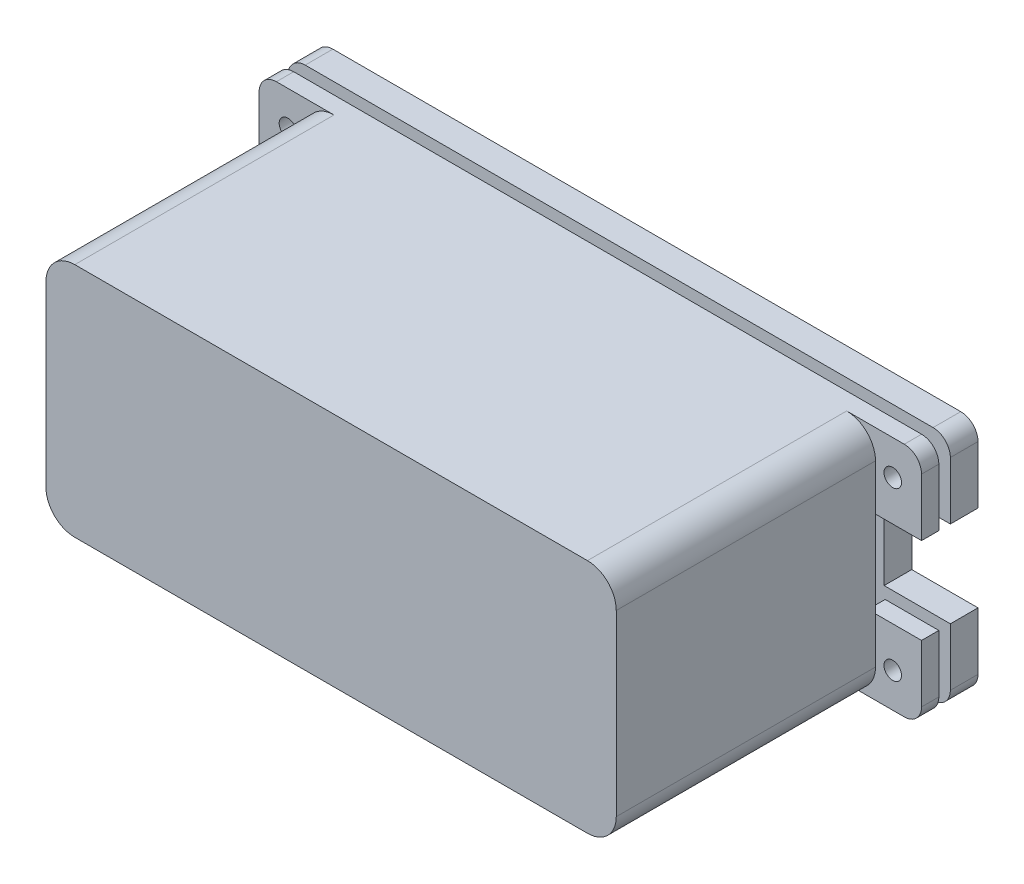
SolidWorks part; units mm, degrees
material "ABS"
ref_plane "前视基准面" through (0, 0, 0) normal (0, 0, 1) x (1, 0, 0)
ref_plane "上视基准面" through (0, 0, 0) normal (0, 1, 0) x (1, 0, 0)
ref_plane "右视基准面" through (0, 0, 0) normal (1, 0, 0) x (0, 0, -1)
other "Configuration Table"
sketch "草图1" plane through (0, 0, 0) normal (0, 0, 1) x (1, 0, 0)
  line L1 (-57.5, -20.5) -> (57.5, -20.5)
  line L2 (-57.5, -20.5) -> (-57.5, 20.5)
  line L3 (-57.5, 20.5) -> (57.5, 20.5)
  line L4 (57.5, -20.5) -> (57.5, 20.5)
  line L5 (-57.5, -20.5) -> (57.5, 20.5) construction
  line L6 (-57.5, 20.5) -> (57.5, -20.5) construction
  point P0 (0, 0)
  dimension "D1" = 115
  dimension "D2" = 41
extrude "凸台-拉伸1" add sketch "草图1" along normal blind 4.8
fillet "圆角1" radius 3 4 edges at (-57.5, -20.5, 2.4) (-57.5, 20.5, 2.4) (57.5, -20.5, 2.4) (57.5, 20.5, 2.4)
sketch "草图2" plane through (0, 0, 4.8) normal (0, 0, 1) x (1, 0, 0)
  line L0 (57.5, -17.5) -> (57.5, 17.5) construction
  line L1 (51, -7.5) -> (64, -7.5)
  line L2 (51, -7.5) -> (51, 7.5)
  line L3 (51, 7.5) -> (64, 7.5)
  line L4 (64, -7.5) -> (64, 7.5)
  line L5 (51, -7.5) -> (64, 7.5) construction
  line L6 (51, 7.5) -> (64, -7.5) construction
  line L8 (-52.5, -14.5) -> (52.5, -14.5) construction
  line L9 (-52.5, -14.5) -> (-52.5, 14.5) construction
  line L10 (-52.5, 14.5) -> (52.5, 14.5) construction
  line L11 (52.5, -14.5) -> (52.5, 14.5) construction
  line L12 (-52.5, -14.5) -> (52.5, 14.5) construction
  line L13 (-52.5, 14.5) -> (52.5, -14.5) construction
  circle A0 centre (52.5, 14.5) radius 1.52
  circle A1 centre (-52.5, 14.5) radius 1.52
  circle A2 centre (-52.5, -14.5) radius 1.52
  circle A3 centre (52.5, -14.5) radius 1.52
  point P0 (57.5, 0)
  point P7 (0, 0)
  dimension "D5" = 3.04
  dimension "D1" = 105
  dimension "D2" = 29
  dimension "D3" = 13
  dimension "D4" = 15
extrude "切除-拉伸1" cut sketch "草图2" against normal blind 55
ref_plane "基准面1" through (0, 0, 6.8) normal (0, 0, 1) x (1, 0, 0)
sketch "草图4" plane through (0, 0, 6.8) normal (0, 0, 1) x (1, 0, 0)
  line L8 (57.5, -17.5) -> (57.5, -7.5)
  line L9 (57.5, -7.5) -> (51, -7.5)
  line L10 (51, -7.5) -> (51, 7.5)
  line L11 (51, 7.5) -> (57.5, 7.5)
  line L12 (57.5, 7.5) -> (57.5, 17.5)
  line L13 (54.5, 20.5) -> (-54.5, 20.5)
  line L14 (-57.5, 17.5) -> (-57.5, -17.5)
  line L15 (-54.5, -20.5) -> (54.5, -20.5)
  line L16 (57.5, -17.5) -> (57.5, -7.5)
  line L17 (57.5, -7.5) -> (51, -7.5)
  line L18 (51, -7.5) -> (51, 7.5)
  line L19 (51, 7.5) -> (57.5, 7.5)
  line L20 (57.5, 7.5) -> (57.5, 17.5)
  line L21 (54.5, 20.5) -> (-54.5, 20.5)
  line L22 (-57.5, 17.5) -> (-57.5, -17.5)
  line L23 (-54.5, -20.5) -> (54.5, -20.5)
  arc A4 (57.5, 17.5) -> (54.5, 20.5) centre (54.5, 17.5) ccw
  arc A5 (-54.5, 20.5) -> (-57.5, 17.5) centre (-54.5, 17.5) ccw
  arc A6 (-57.5, -17.5) -> (-54.5, -20.5) centre (-54.5, -17.5) ccw
  arc A7 (54.5, -20.5) -> (57.5, -17.5) centre (54.5, -17.5) ccw
  arc A8 (57.5, 17.5) -> (54.5, 20.5) centre (54.5, 17.5) ccw
  arc A9 (-54.5, 20.5) -> (-57.5, 17.5) centre (-54.5, 17.5) ccw
  arc A10 (-57.5, -17.5) -> (-54.5, -20.5) centre (-54.5, -17.5) ccw
  arc A11 (54.5, -20.5) -> (57.5, -17.5) centre (54.5, -17.5) ccw
  dimension "D1" = 0
extrude "凸台-拉伸2" add sketch "草图4" along normal blind 3 separate body
sketch "草图5" plane through (0, 0, 9.8) normal (0, 0, 1) x (1, 0, 0)
  line L0 (54.5, 20.5) -> (-54.5, 20.5) construction
  line L1 (-49.5, -20.5) -> (49.5, -20.5)
  line L2 (-49.5, -20.5) -> (-49.5, 20.5)
  line L3 (-49.5, 20.5) -> (49.5, 20.5)
  line L4 (49.5, -20.5) -> (49.5, 20.5)
  line L5 (-49.5, -20.5) -> (49.5, 20.5) construction
  line L6 (-49.5, 20.5) -> (49.5, -20.5) construction
  circle A0 centre (52.5, 14.5) radius 1.52 construction
  point P0 (0, 0)
  dimension "D1" = 3
extrude "凸台-拉伸3" add sketch "草图5" along normal blind 45
sketch "草图7" plane through (0, 0, 9.8) normal (0, 0, 1) x (1, 0, 0)
  circle A0 centre (-52.5, -14.5) radius 1.52 construction
  circle A1 centre (-52.5, 14.5) radius 1.52 construction
  circle A2 centre (52.5, -14.5) radius 1.52 construction
  circle A3 centre (52.5, 14.5) radius 1.52 construction
  circle A4 centre (-52.5, -14.5) radius 1.52
  circle A5 centre (-52.5, 14.5) radius 1.52
  circle A6 centre (52.5, -14.5) radius 1.52
  circle A7 centre (52.5, 14.5) radius 1.52
extrude "切除-拉伸2" cut sketch "草图7" against normal blind 45
fillet "圆角2" radius 5 4 edges at (49.5, 20.5, 32.3) (-49.5, 20.5, 32.3) (-49.5, -20.5, 32.3) (49.5, -20.5, 32.3)
sketch "草图8" plane through (0, 0, 6.8) normal (0, 0, -1) x (-1, 0, 0)
  line L8 (-48.18, 15.5) -> (-48.18, -15.5)
  line L9 (44.5, 19.18) -> (-44.5, 19.18)
  line L10 (48.18, -15.5) -> (48.18, 15.5)
  line L11 (-44.5, -19.18) -> (44.5, -19.18)
  line L12 (-48.18, 15.5) -> (-48.18, -15.5)
  line L13 (44.5, 19.18) -> (-44.5, 19.18)
  line L14 (48.18, -15.5) -> (48.18, 15.5)
  line L15 (-44.5, -19.18) -> (44.5, -19.18)
  arc A4 (48.18, 15.5) -> (44.5, 19.18) centre (44.5, 15.5) ccw
  arc A5 (48.18, 15.5) -> (44.5, 19.18) centre (44.5, 15.5) ccw
  arc A6 (44.5, -19.18) -> (48.18, -15.5) centre (44.5, -15.5) ccw
  arc A7 (44.5, -19.18) -> (48.18, -15.5) centre (44.5, -15.5) ccw
  arc A8 (-48.18, -15.5) -> (-44.5, -19.18) centre (-44.5, -15.5) ccw
  arc A9 (-48.18, -15.5) -> (-44.5, -19.18) centre (-44.5, -15.5) ccw
  arc A10 (-44.5, 19.18) -> (-48.18, 15.5) centre (-44.5, 15.5) ccw
  arc A11 (-44.5, 19.18) -> (-48.18, 15.5) centre (-44.5, 15.5) ccw
  dimension "D1" = 1.32
extrude "切除-拉伸4" cut sketch "草图8" against normal blind 43
sketch "草图9" plane through (0, 0, 0) normal (0, 0, -1) x (-1, 0, 0)
  line L0 (-57.5, -7.5) -> (-51, -7.5) construction
  line L1 (-51, 7.5) -> (-46, 7.5)
  line L2 (-51, 7.5) -> (-51, -7.5)
  line L3 (-51, -7.5) -> (-46, -7.5)
  line L4 (-46, 7.5) -> (-46, -7.5)
  dimension "D1" = 5
extrude "切除-拉伸5" cut sketch "草图9" against normal up to surface (9.8 mm away) up to face at (54.02, -14.5, 9.8)
